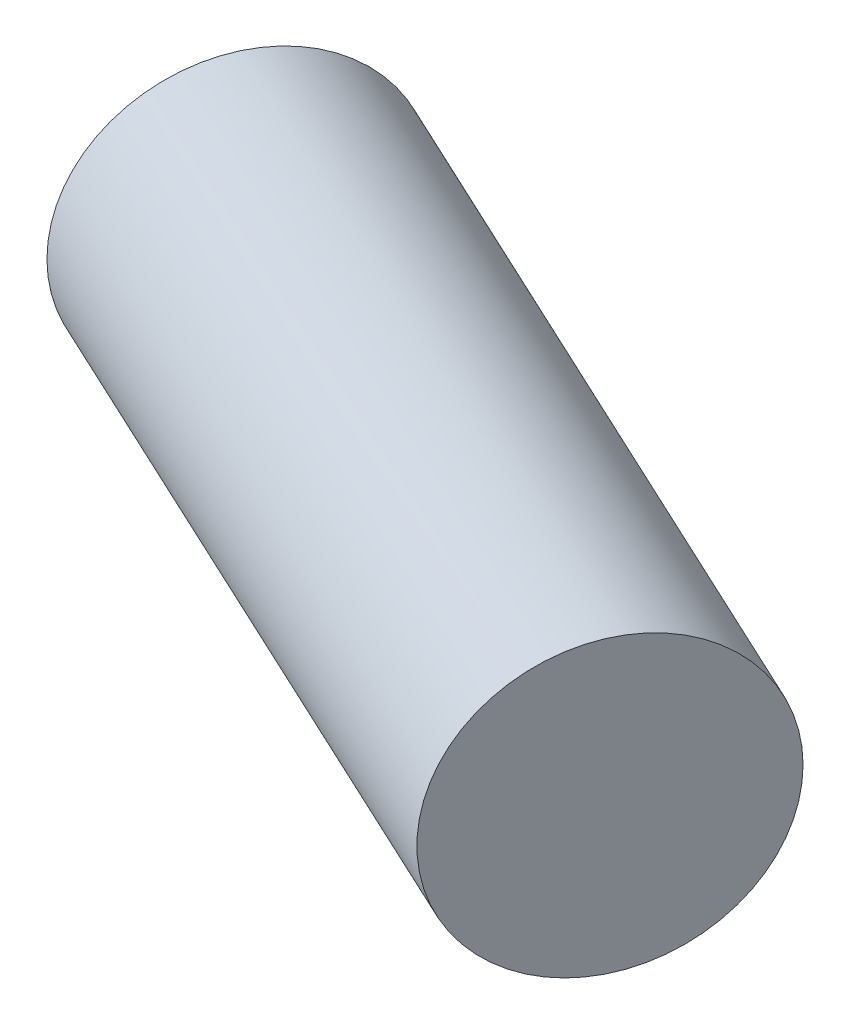
SolidWorks part; units mm, degrees
ref_plane "Alzado" through (0, 0, 0) normal (0, 0, 1) x (1, 0, 0)
ref_plane "Planta" through (0, 0, 0) normal (0, 1, 0) x (1, 0, 0)
ref_plane "Vista lateral" through (0, 0, 0) normal (1, 0, 0) x (0, 0, -1)
sketch "Sketch1" plane through (3.578, 0, 1.6684) normal (0.9063, 0, 0.4226) x (0.4226, 0, -0.9063)
  circle A0 centre (-63.062, 101.4969) radius 1.5
extrude "Boss-Extrude1" add sketch "Sketch1" against normal up to surface (7.8958 mm away)
